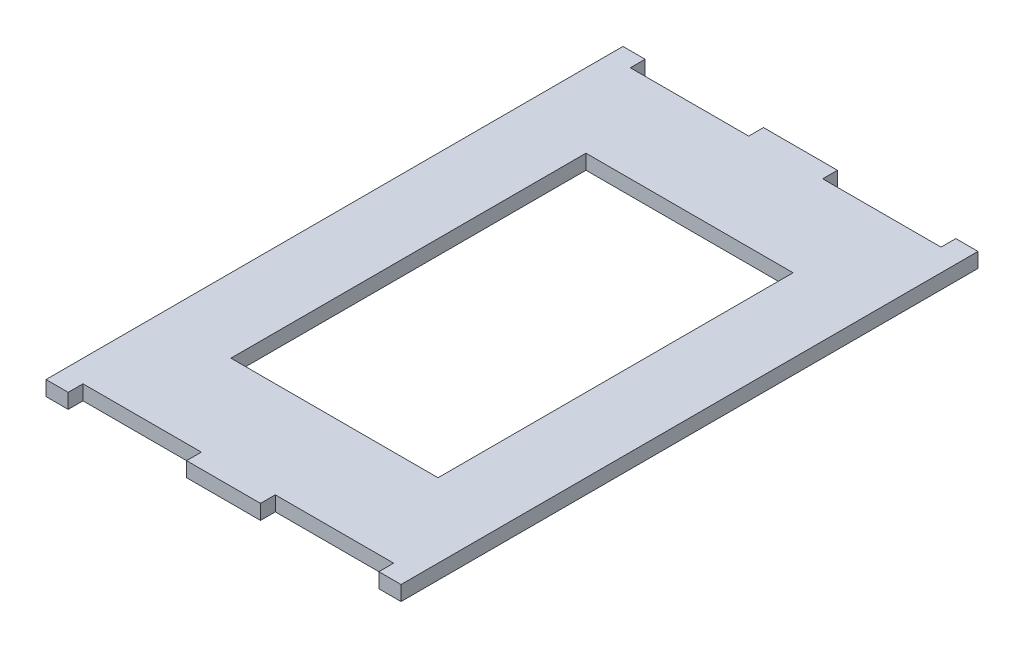
SolidWorks part; units mm, degrees
ref_plane "Plan de face" through (0, 0, 0) normal (0, 0, 1) x (1, 0, 0)
ref_plane "Plan de dessus" through (0, 0, 0) normal (0, 1, 0) x (1, 0, 0)
ref_plane "Plan de droite" through (0, 0, 0) normal (1, 0, 0) x (0, 0, -1)
sketch "Esquisse1" plane through (0, 0, 0) normal (0, 1, 0) x (1, 0, 0)
  line L0 (0, 0) -> (240, 0) construction
  line L1 (240, 0) -> (240, 10) construction
  line L2 (240, 10) -> (0, 10) construction
  line L3 (0, 10) -> (0, 0) construction
  line L4 (0, 10) -> (15, 10) construction
  line L5 (15, 10) -> (15, 0)
  line L6 (15, 0) -> (95, 0) construction
  line L7 (95, 0) -> (95, 10)
  line L8 (95, 10) -> (145, 10) construction
  line L9 (145, 10) -> (145, 0)
  line L10 (145, 0) -> (225, 0) construction
  line L11 (225, 0) -> (225, 10)
  line L12 (225, 10) -> (240, 10) construction
  line L13 (120, 10) -> (120, 0) construction
  line L14 (0, 10) -> (0, 380)
  line L15 (0, 195) -> (240, 195) construction
  line L16 (240, 380) -> (240, 10)
  line L17 (225, 380) -> (240, 380) construction
  line L18 (225, 390) -> (225, 380)
  line L19 (145, 390) -> (225, 390) construction
  line L20 (145, 380) -> (145, 390)
  line L21 (95, 380) -> (145, 380) construction
  line L22 (95, 390) -> (95, 380)
  line L23 (15, 390) -> (95, 390) construction
  line L24 (15, 380) -> (15, 390)
  line L25 (0, 380) -> (15, 380) construction
  line L26 (0, 380) -> (0, 390)
  line L27 (50, 315) -> (190, 315)
  line L28 (50, 315) -> (50, 75)
  line L29 (50, 75) -> (190, 75)
  line L30 (190, 315) -> (190, 75)
  line L31 (0, 390) -> (15, 390)
  line L32 (15, 380) -> (95, 380)
  line L33 (95, 390) -> (145, 390)
  line L34 (145, 380) -> (225, 380)
  line L35 (225, 390) -> (240, 390)
  line L36 (240, 390) -> (240, 380)
  line L37 (240, 10) -> (240, 0)
  line L38 (240, 0) -> (225, 0)
  line L39 (225, 10) -> (145, 10)
  line L40 (145, 0) -> (95, 0)
  line L41 (95, 10) -> (15, 10)
  line L42 (15, 0) -> (0, 0)
  line L43 (0, 10) -> (0, 0)
  point P31 (190, 195)
  dimension "D1" = 50
  dimension "D2" = 10
  dimension "D3" = 240
  dimension "D4" = 80
  dimension "D5" = 80
  dimension "D6" = 195
  dimension "D7" = 50
  dimension "D8" = 50
  dimension "D9" = 65
extrude "Boss.-Extru.1" add sketch "Esquisse1" along normal blind 10
